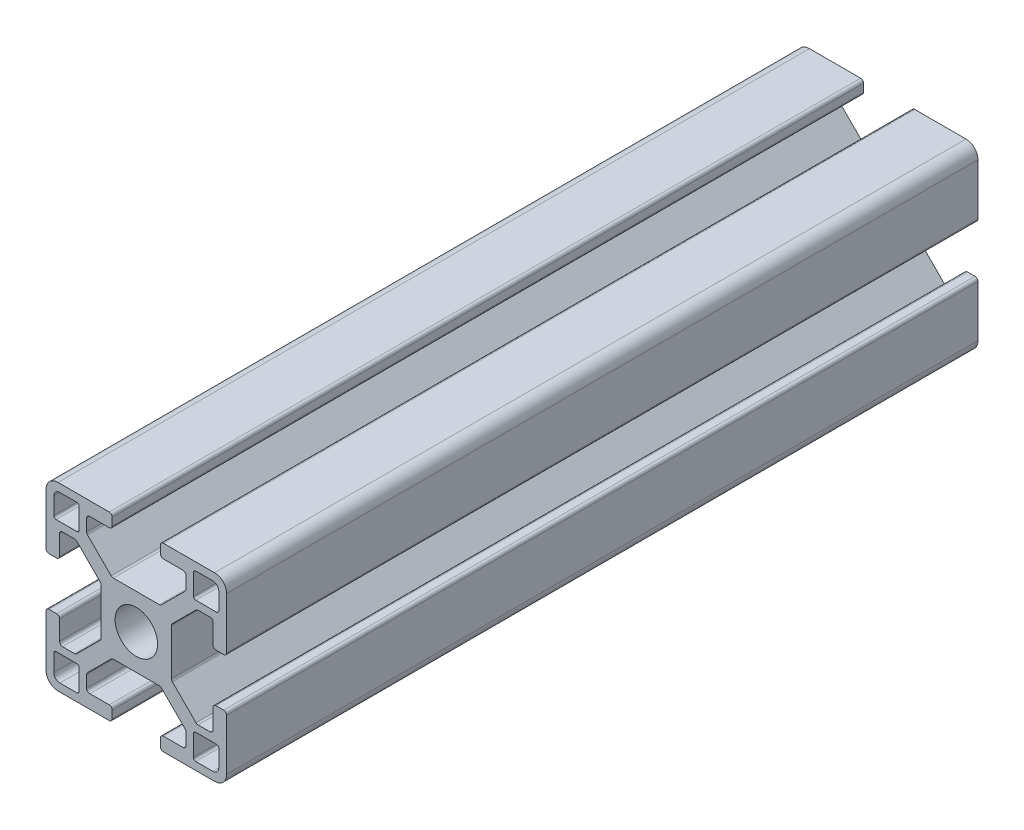
SolidWorks part; units mm, degrees
ref_plane "Front Plane" through (0, 0, 0) normal (0, 0, 1) x (1, 0, 0)
ref_plane "Top Plane" through (0, 0, 0) normal (0, 1, 0) x (1, 0, 0)
ref_plane "Right Plane" through (0, 0, 0) normal (1, 0, 0) x (0, 0, -1)
sketch "Sketch1" plane through (0, 0, 0) normal (0, 0, 1) x (1, 0, 0)
  line L0 (3.9799, -2.4733) -> (3.1981, -1.4942) construction
  line L1 (1.4942, -3.1981) -> (2.4733, -3.9799) construction
  line L2 (-2.4733, -3.9799) -> (-1.4942, -3.1981) construction
  line L3 (-3.1981, -1.4942) -> (-3.9799, -2.4733) construction
  line L4 (-3.9799, 2.4733) -> (-3.1981, 1.4942) construction
  line L5 (-1.4942, 3.1981) -> (-2.4733, 3.9799) construction
  line L6 (2.4733, 3.9799) -> (1.4942, 3.1981) construction
  line L7 (3.1981, 1.4942) -> (3.9799, 2.4733) construction
  line L8 (-12.6999, -13.6999) -> (-9.881, -13.6999)
  line L9 (-13.6999, -9.881) -> (-13.6999, -12.6999)
  line L10 (-9.88, -9.5) -> (-13.3189, -9.5)
  line L11 (-9.5, -13.3189) -> (-9.5, -9.88)
  line L12 (13.6999, -12.6999) -> (13.6999, -9.881)
  line L13 (9.881, -13.6999) -> (12.6999, -13.6999)
  line L14 (9.5, -9.88) -> (9.5, -13.3189)
  line L15 (13.3189, -9.5) -> (9.88, -9.5)
  line L16 (9.88, 9.5) -> (13.3189, 9.5)
  line L17 (9.5, 13.3189) -> (9.5, 9.88)
  line L18 (12.6999, 13.6999) -> (9.881, 13.6999)
  line L19 (13.6999, 9.881) -> (13.6999, 12.6999)
  line L20 (-13.6999, 12.6999) -> (-13.6999, 9.881)
  line L21 (-9.881, 13.6999) -> (-12.6999, 13.6999)
  line L22 (-9.5, 9.88) -> (-9.5, 13.3189)
  line L23 (-13.3189, 9.5) -> (-9.88, 9.5)
  line L24 (14.4999, -4) -> (13.2425, -4)
  line L25 (12.7425, -4.5) -> (12.7425, -7.7325)
  line L26 (12.2428, -8.25) -> (10.2602, -8.25)
  line L27 (9.9066, -8.1035) -> (5.9811, -4.178)
  line L28 (5.8347, -3.8245) -> (5.8347, -1.0125)
  line L29 (5.8347, -1.0125) -> (5.3247, -0.0625) construction
  line L30 (5.3247, -0.0625) -> (5.8347, 0.8875) construction
  line L31 (5.8347, 0.8875) -> (5.8347, 3.8245)
  line L32 (5.9811, 4.178) -> (9.9066, 8.1035)
  line L33 (10.2602, 8.25) -> (12.2428, 8.25)
  line L34 (12.7425, 7.7325) -> (12.7425, 4.5)
  line L35 (13.2425, 4) -> (14.4999, 4)
  line L36 (14.9999, 4.5) -> (14.9999, 12.9999)
  line L37 (12.9999, 14.9999) -> (4.5, 14.9999)
  line L38 (4, 14.4999) -> (4, 13.2425)
  line L39 (4.5, 12.7425) -> (7.7325, 12.7425)
  line L40 (8.25, 12.2428) -> (8.25, 10.2602)
  line L41 (8.1035, 9.9066) -> (4.178, 5.9811)
  line L42 (3.8245, 5.8347) -> (0.95, 5.8347)
  line L43 (0.95, 5.8347) -> (0, 5.3247) construction
  line L44 (0, 5.3247) -> (-0.95, 5.8347) construction
  line L45 (-0.95, 5.8347) -> (-3.8245, 5.8347)
  line L46 (-4.178, 5.9811) -> (-8.1035, 9.9066)
  line L47 (-8.25, 10.2602) -> (-8.25, 12.2428)
  line L48 (-7.7325, 12.7425) -> (-4.5, 12.7425)
  line L49 (-4, 13.2425) -> (-4, 14.4999)
  line L50 (-4.5, 14.9999) -> (-12.9999, 14.9999)
  line L51 (-14.9999, 12.9999) -> (-14.9999, 4.5)
  line L52 (-14.4999, 4) -> (-13.2425, 4)
  line L53 (-12.7425, 4.5) -> (-12.7425, 7.7325)
  line L54 (-12.2428, 8.25) -> (-10.2602, 8.25)
  line L55 (-9.9066, 8.1035) -> (-5.9811, 4.178)
  line L56 (-5.8347, 3.8245) -> (-5.8347, 0.8875)
  line L57 (-5.8347, 0.8875) -> (-5.3247, -0.0625) construction
  line L58 (-5.3247, -0.0625) -> (-5.8347, -1.0125) construction
  line L59 (-5.8347, -1.0125) -> (-5.8347, -3.8245)
  line L60 (-5.9811, -4.178) -> (-9.9066, -8.1035)
  line L61 (-10.2602, -8.25) -> (-12.2428, -8.25)
  line L62 (-12.7425, -7.7325) -> (-12.7425, -4.5)
  line L63 (-13.2425, -4) -> (-14.4999, -4)
  line L64 (-14.9999, -4.5) -> (-14.9999, -12.9999)
  line L65 (-12.9999, -14.9999) -> (-4.5, -14.9999)
  line L66 (-4, -14.4999) -> (-4, -13.2425)
  line L67 (-4.5, -12.7425) -> (-7.7325, -12.7425)
  line L68 (-8.25, -12.2428) -> (-8.25, -10.2602)
  line L69 (-8.1035, -9.9066) -> (-4.178, -5.9811)
  line L70 (-3.8245, -5.8347) -> (-0.95, -5.8347)
  line L71 (-0.95, -5.8347) -> (0, -5.3247) construction
  line L72 (0, -5.3247) -> (0.95, -5.8347) construction
  line L73 (0.95, -5.8347) -> (3.8245, -5.8347)
  line L74 (4.178, -5.9811) -> (8.1035, -9.9066)
  line L75 (8.25, -10.2602) -> (8.25, -12.2428)
  line L76 (7.7325, -12.7425) -> (4.5, -12.7425)
  line L77 (4, -13.2425) -> (4, -14.4999)
  line L78 (4.5, -14.9999) -> (12.9999, -14.9999)
  line L79 (14.9999, -12.9999) -> (14.9999, -4.5)
  line L80 (-5.8347, -1.0125) -> (-5.8347, 0.8875)
  line L81 (-0.95, 5.8347) -> (0.95, 5.8347)
  line L82 (5.8347, 0.8875) -> (5.8347, -1.0125)
  line L83 (-0.95, -5.8347) -> (0.95, -5.8347)
  arc A0 (2.4733, -3.9799) -> (3.9799, -2.4733) centre (3.1422, -3.1422) ccw construction
  arc A1 (-1.4942, -3.1981) -> (1.4942, -3.1981) centre (0, 0) ccw construction
  arc A2 (-3.9799, -2.4733) -> (-2.4733, -3.9799) centre (-3.1422, -3.1422) ccw construction
  arc A3 (-3.1981, 1.4942) -> (-3.1981, -1.4942) centre (0, 0) ccw construction
  arc A4 (-2.4733, 3.9799) -> (-3.9799, 2.4733) centre (-3.1422, 3.1422) ccw construction
  arc A5 (1.4942, 3.1981) -> (-1.4942, 3.1981) centre (0, 0) ccw construction
  arc A6 (3.9799, 2.4733) -> (2.4733, 3.9799) centre (3.1422, 3.1422) ccw construction
  arc A7 (3.1981, -1.4942) -> (3.1981, 1.4942) centre (0, 0) ccw construction
  arc A8 (-13.6999, -12.6999) -> (-12.6999, -13.6999) centre (-12.6999, -12.6999) ccw
  arc A9 (-13.3189, -9.5) -> (-13.6999, -9.881) centre (-13.3189, -9.881) ccw
  arc A10 (-9.5, -9.88) -> (-9.88, -9.5) centre (-9.88, -9.88) ccw
  arc A11 (-9.881, -13.6999) -> (-9.5, -13.3189) centre (-9.881, -13.3189) ccw
  arc A12 (12.6999, -13.6999) -> (13.6999, -12.6999) centre (12.6999, -12.6999) ccw
  arc A13 (9.5, -13.3189) -> (9.881, -13.6999) centre (9.881, -13.3189) ccw
  arc A14 (9.88, -9.5) -> (9.5, -9.88) centre (9.88, -9.88) ccw
  arc A15 (13.6999, -9.881) -> (13.3189, -9.5) centre (13.3189, -9.881) ccw
  arc A16 (9.5, 9.88) -> (9.88, 9.5) centre (9.88, 9.88) ccw
  arc A17 (9.881, 13.6999) -> (9.5, 13.3189) centre (9.881, 13.3189) ccw
  arc A18 (13.6999, 12.6999) -> (12.6999, 13.6999) centre (12.6999, 12.6999) ccw
  arc A19 (13.3189, 9.5) -> (13.6999, 9.881) centre (13.3189, 9.881) ccw
  arc A20 (14.9999, -4.5) -> (14.4999, -4) centre (14.4999, -4.5) ccw
  arc A21 (13.2425, -4) -> (12.7425, -4.5) centre (13.2425, -4.5) ccw
  arc A22 (12.2428, -8.25) -> (12.7425, -7.7325) centre (12.2428, -7.75) ccw
  arc A23 (9.9066, -8.1035) -> (10.2602, -8.25) centre (10.2602, -7.75) ccw
  arc A24 (5.8347, -3.8245) -> (5.9811, -4.178) centre (6.3347, -3.8245) ccw
  arc A25 (5.9811, 4.178) -> (5.8347, 3.8245) centre (6.3347, 3.8245) ccw
  arc A26 (10.2602, 8.25) -> (9.9066, 8.1035) centre (10.2602, 7.75) ccw
  arc A27 (12.7425, 7.7325) -> (12.2428, 8.25) centre (12.2428, 7.75) ccw
  arc A28 (12.7425, 4.5) -> (13.2425, 4) centre (13.2425, 4.5) ccw
  arc A29 (14.4999, 4) -> (14.9999, 4.5) centre (14.4999, 4.5) ccw
  arc A30 (14.9999, 12.9999) -> (12.9999, 14.9999) centre (12.9999, 12.9999) ccw
  arc A31 (4.5, 14.9999) -> (4, 14.4999) centre (4.5, 14.4999) ccw
  arc A32 (4, 13.2425) -> (4.5, 12.7425) centre (4.5, 13.2425) ccw
  arc A33 (8.25, 12.2428) -> (7.7325, 12.7425) centre (7.75, 12.2428) ccw
  arc A34 (8.1035, 9.9066) -> (8.25, 10.2602) centre (7.75, 10.2602) ccw
  arc A35 (3.8245, 5.8347) -> (4.178, 5.9811) centre (3.8245, 6.3347) ccw
  arc A36 (-4.178, 5.9811) -> (-3.8245, 5.8347) centre (-3.8245, 6.3347) ccw
  arc A37 (-8.25, 10.2602) -> (-8.1035, 9.9066) centre (-7.75, 10.2602) ccw
  arc A38 (-7.7325, 12.7425) -> (-8.25, 12.2428) centre (-7.75, 12.2428) ccw
  arc A39 (-4.5, 12.7425) -> (-4, 13.2425) centre (-4.5, 13.2425) ccw
  arc A40 (-4, 14.4999) -> (-4.5, 14.9999) centre (-4.5, 14.4999) ccw
  arc A41 (-12.9999, 14.9999) -> (-14.9999, 12.9999) centre (-12.9999, 12.9999) ccw
  arc A42 (-14.9999, 4.5) -> (-14.4999, 4) centre (-14.4999, 4.5) ccw
  arc A43 (-13.2425, 4) -> (-12.7425, 4.5) centre (-13.2425, 4.5) ccw
  arc A44 (-12.2428, 8.25) -> (-12.7425, 7.7325) centre (-12.2428, 7.75) ccw
  arc A45 (-9.9066, 8.1035) -> (-10.2602, 8.25) centre (-10.2602, 7.75) ccw
  arc A46 (-5.8347, 3.8245) -> (-5.9811, 4.178) centre (-6.3347, 3.8245) ccw
  arc A47 (-5.9811, -4.178) -> (-5.8347, -3.8245) centre (-6.3347, -3.8245) ccw
  arc A48 (-10.2602, -8.25) -> (-9.9066, -8.1035) centre (-10.2602, -7.75) ccw
  arc A49 (-12.7425, -7.7325) -> (-12.2428, -8.25) centre (-12.2428, -7.75) ccw
  arc A50 (-12.7425, -4.5) -> (-13.2425, -4) centre (-13.2425, -4.5) ccw
  arc A51 (-14.4999, -4) -> (-14.9999, -4.5) centre (-14.4999, -4.5) ccw
  arc A52 (-14.9999, -12.9999) -> (-12.9999, -14.9999) centre (-12.9999, -12.9999) ccw
  arc A53 (-4.5, -14.9999) -> (-4, -14.4999) centre (-4.5, -14.4999) ccw
  arc A54 (-4, -13.2425) -> (-4.5, -12.7425) centre (-4.5, -13.2425) ccw
  arc A55 (-8.25, -12.2428) -> (-7.7325, -12.7425) centre (-7.75, -12.2428) ccw
  arc A56 (-8.1035, -9.9066) -> (-8.25, -10.2602) centre (-7.75, -10.2602) ccw
  arc A57 (-3.8245, -5.8347) -> (-4.178, -5.9811) centre (-3.8245, -6.3347) ccw
  arc A58 (4.178, -5.9811) -> (3.8245, -5.8347) centre (3.8245, -6.3347) ccw
  arc A59 (8.25, -10.2602) -> (8.1035, -9.9066) centre (7.75, -10.2602) ccw
  arc A60 (7.7325, -12.7425) -> (8.25, -12.2428) centre (7.75, -12.2428) ccw
  arc A61 (4.5, -12.7425) -> (4, -13.2425) centre (4.5, -13.2425) ccw
  arc A62 (4, -14.4999) -> (4.5, -14.9999) centre (4.5, -14.4999) ccw
  arc A63 (12.9999, -14.9999) -> (14.9999, -12.9999) centre (12.9999, -12.9999) ccw
  arc A64 (-12.6999, 13.6999) -> (-13.6999, 12.6999) centre (-12.6999, 12.6999) ccw
  arc A65 (-9.5, 13.3189) -> (-9.881, 13.6999) centre (-9.881, 13.3189) ccw
  arc A66 (-9.88, 9.5) -> (-9.5, 9.88) centre (-9.88, 9.88) ccw
  arc A67 (-13.6999, 9.881) -> (-13.3189, 9.5) centre (-13.3189, 9.881) ccw
  circle A68 centre (0, 0) radius 3.53
extrude "Boss-Extrude1" add sketch "Sketch1" along normal mid plane 124.7925
